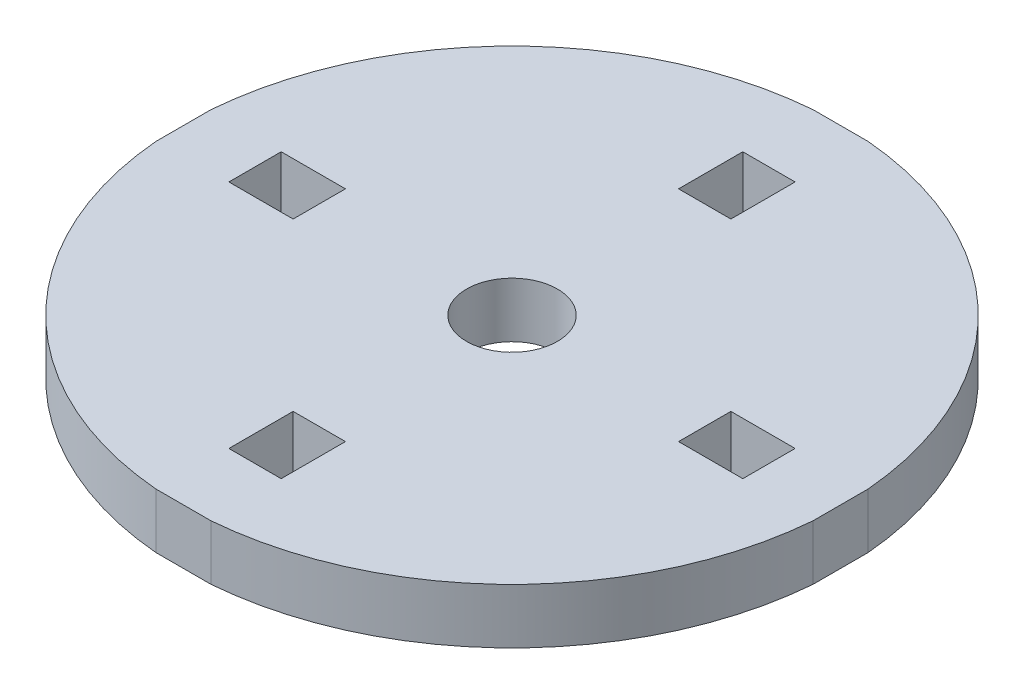
SolidWorks part; units mm, degrees
ref_plane "Front Plane" through (0, 0, 0) normal (0, 0, 1) x (1, 0, 0)
ref_plane "Top Plane" through (0, 0, 0) normal (0, 1, 0) x (1, 0, 0)
ref_plane "Right Plane" through (0, 0, 0) normal (1, 0, 0) x (0, 0, -1)
sketch "Sketch1" plane through (0, 0, 0) normal (0, 1, 0) x (1, 0, 0)
  line L0 (-1.5, -17.9) -> (1.5, -17.9)
  line L1 (0, -95) -> (0, 0) construction
  line L2 (-1.5, -18) -> (1.5, -18) construction
  line L3 (0, -14) -> (0, -10.5) construction
  line L4 (0, -18) -> (0, -17.9) construction
  line L5 (1.425, -14) -> (-1.425, -14)
  line L6 (1.425, -14) -> (1.425, -10.5)
  line L7 (1.425, -10.5) -> (-1.425, -10.5)
  line L8 (-1.425, -14) -> (-1.425, -10.5)
  line L9 (0, -10.5) -> (0, -14) construction
  line L10 (1.425, -12.25) -> (-1.425, -12.25) construction
  line L13 (-17.9, 1.5) -> (-17.9, -1.5)
  line L14 (1.5, 17.9) -> (-1.5, 17.9)
  line L15 (17.9, -1.5) -> (17.9, 1.5)
  line L16 (-10.5, -1.425) -> (-10.5, 1.425)
  line L17 (-14, 1.425) -> (-10.5, 1.425)
  line L18 (-14, -1.425) -> (-14, 1.425)
  line L19 (-14, -1.425) -> (-10.5, -1.425)
  line L20 (-1.425, 10.5) -> (1.425, 10.5)
  line L21 (1.425, 14) -> (1.425, 10.5)
  line L22 (-1.425, 14) -> (1.425, 14)
  line L23 (-1.425, 14) -> (-1.425, 10.5)
  line L24 (10.5, 1.425) -> (10.5, -1.425)
  line L25 (14, -1.425) -> (10.5, -1.425)
  line L26 (14, 1.425) -> (14, -1.425)
  line L27 (14, 1.425) -> (10.5, 1.425)
  circle A0 centre (0, 0) radius 2.475
  arc A2 (-17.9, -1.5) -> (-1.5, -17.9) centre (0, 0) ccw
  arc A3 (-17.9, 1.5) -> (-1.5, 17.9) centre (0, 0) cw
  arc A4 (1.5, 17.9) -> (17.9, 1.5) centre (0, 0) cw
  arc A5 (17.9, -1.5) -> (1.5, -17.9) centre (0, 0) cw
  point P5 (0, -17.9)
  point P6 (0, -12.25)
  point P11 (0, -12.25)
  point P32 (0, 0)
  point P49 (0, 0)
  dimension "D1" = 4.95
  dimension "D2" = 0.1
  dimension "D3" = 2.85
  dimension "D4" = 3
  dimension "D5" = 4
  dimension "D6" = 4
extrude "Boss-Extrude1" add sketch "Sketch1" along normal blind 3
